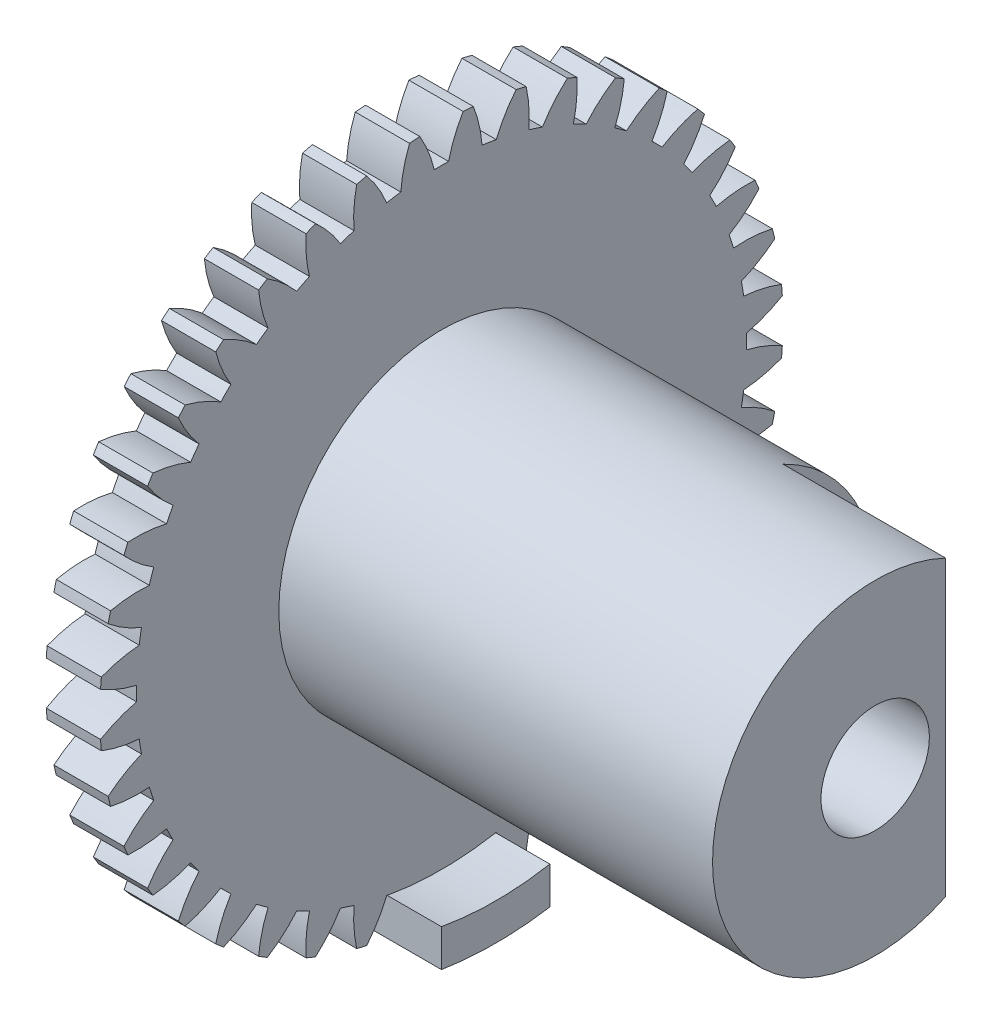
SolidWorks part; units mm, degrees
ref_plane "Plane1" through (0, 0, 0) normal (0, 0, 1) x (1, 0, 0)
ref_plane "Plane2" through (0, 0, 0) normal (0, 1, 0) x (1, 0, 0)
ref_plane "Plane3" through (0, 0, 0) normal (1, 0, 0) x (0, 0, -1)
sketch "HoldingSke" plane through (0, 0, 0) normal (0, 1, 0) x (1, 0, 0)
  line L0 (0, 0) -> (2.5535, -2.1426)
  line L1 (-15, 0) -> (100, 0) construction
  line L2 (0, 0) -> (-2.1039, 2.3779)
  line L3 (0, 0) -> (-11.863, 4.5341)
  line L4 (0, 0) -> (6.6156, 5.5511)
  line L5 (0, 0) -> (-46.8476, -17.4728)
  line L6 (0, 0) -> (-0.829, -0.5593)
  line L7 (-2.1039, 2.3779) -> (8.6586, 51.2059)
  line L8 (-76.2, 54.61) -> (-75.9, 54.61)
  line L9 (-71.009, 38.7566) -> (-53.1078, 45.2721)
  line L10 (-76.2, 71.12) -> (104.1128, 71.12)
  line L11 (0, 0) -> (-1, 0)
  line L12 (-76.2, 101.6) -> (-76.19, 101.6)
  line L13 (24.9733, 27.94) -> (52.9518, 28.4284)
  line L14 (24.9733, 27.94) -> (24.9743, 27.94)
  line L15 (24.9733, 27.94) -> (100.4006, 29.5858)
  line L16 (-63.627, -0.3) -> (-12.827, -0.3)
  circle A0 centre (0, 0) radius 1
  circle A1 centre (0, 0) radius 5.624
  circle A2 centre (0, 0) radius 37.5
  circle A3 centre (0, 0) radius 1
  dimension "MHD" = 11.248
  dimension "Hub_dia" = 75
  dimension "Bore" = 2
  dimension "MBD" = 2
  dimension "Num_teeth" = 40
  dimension "Pitch" = 3.3333
  dimension "Overall_len" = 50
  dimension "Show_teeth" = 40
  dimension "Thickness" = 1
  dimension "OAL" = 50.0001
  dimension "T_dim" = 0.3
  dimension "Ap" = 20
  dimension "H" = 19.05
  dimension "Pitch_radius" = 180.3128
  dimension "Width" = 1
  dimension "Backlash" = 0.01
  dimension "Addendum_fac" = 1
  dimension "Dedendum_fac" = 1.25
  dimension "Clearance_fac" = 0.25
  dimension "Dedendum_add" = 0.001
  dimension "Module" = 0.3
sketch "BasProSke" plane through (0, 0, 0) normal (0, 1, 0) x (1, 0, 0)
  line L0 (-10, 0) -> (60, 0) construction
  line L1 (0, 0) -> (0, 6.3)
  line L2 (0, 0) -> (1, 0)
  line L3 (1, 0) -> (1, 6.3)
  line L4 (1, 6.3) -> (0, 6.3)
  dimension "Thickness" = 1
  dimension "Diameter" = 12.6
revolve "Base-Revolve" add sketch "BasProSke" angle 360 about L0
sketch "TooCutSke" plane through (0, 0, 0) normal (1, 0, 0) x (0, 0, -1)
  line L1 (0, 0) -> (0, 107) construction
  line L2 (0, 0) -> (-0.2531, 5.9947) construction
  line L3 (0, 0) -> (-0.9409, 11.9551) construction
  line L4 (-0.2531, 5.9947) -> (-0.4704, 5.9776) construction
  arc A0 (0.1321, 5.6224) -> (-0.1321, 5.6224) centre (0, 0) ccw
  arc A1 (0.4141, 6.3118) -> (-0.4141, 6.3118) centre (0, 0) ccw
  circle A2 centre (0, 0) radius 6 construction
  circle A3 centre (0, 0) radius 5.6382 construction
  arc A4 (-0.1321, 5.6224) -> (-0.4141, 6.3118) centre (-2.4676, 5.0695) ccw
  arc A5 (0.4141, 6.3118) -> (0.1321, 5.6224) centre (2.4676, 5.0695) ccw
  dimension "Root_dia" = 11.248
  dimension "Overcut_dia" = 12.6508
  dimension "Pitch_dia" = 12
  dimension "Base_dia" = 11.2763
  dimension "Flank_rad" = 2.4
  dimension "Half_ang" = 4.5
  dimension "Half_CT" = 0.2181
extrude "ToothCut" cut sketch "TooCutSke" along normal through all
fillet "Breaks" [suppressed] radius 0.006
fillet "RootFillets" [suppressed] radius 0.076
pattern_circular "TeethCuts" count 40 every 9 about axis through (-10, 0, 0) along (1, 0, 0) of "ToothCut", "RootFillets", "Breaks"
sketch "HubNeaOneSke" plane through (0, 0, 0) normal (-1, 0, 0) x (0, 0, 1)
  circle A0 centre (0, 0) radius 5.624
  dimension "Diameter" = 11.248
extrude "HubNearOne" [suppressed] add sketch "HubNeaOneSke" along normal blind 49.0001
sketch "HubNeaBotSke" plane through (0, 0, 0) normal (-1, 0, 0) x (0, 0, 1)
  circle A0 centre (0, 0) radius 5.624
  dimension "Diameter" = 11.248
extrude "HubNearBoth" [suppressed] add sketch "HubNeaBotSke" along normal blind 24.5
ref_plane "FarPln" through (1, 0, 0) normal (1, 0, 0) x (0, 0, -1)
sketch "HubFarSke" plane through (1, 0, 0) normal (1, 0, 0) x (0, 0, -1)
  circle A0 centre (0, 0) radius 5.624
  dimension "Diameter" = 11.248
extrude "HubFar" [suppressed] add sketch "HubFarSke" along normal blind 24.5
sketch "BorSke" plane through (0, 0, 0) normal (1, 0, 0) x (0, 0, -1)
  circle A0 centre (0, 0) radius 1
  dimension "Diameter" = 2
extrude "Bore" cut sketch "BorSke" along normal mid plane 100.0001
sketch "KeySke" plane through (0, 0, 0) normal (1, 0, 0) x (0, 0, -1)
  line L0 (-0.4, 0) -> (-0.4, 1.3)
  line L1 (-0.4, 1.3) -> (0.4, 1.3)
  line L2 (0.4, 1.3) -> (0.4, 0)
  line L3 (0, 0) -> (0, 34) construction
  line L4 (-0.4, 0) -> (0.4, 0)
  dimension "Offset" = 1.3
  dimension "Width" = 0.8
extrude "Keyway" [suppressed] cut sketch "KeySke" along normal mid plane 100.0001
pattern_circular "Keyway2" [suppressed] count 2 every 90 about axis through (-10, 0, 0) along (1, 0, 0)
sketch "Schizzo1" plane through (1, 0, 0) normal (1, 0, 0) x (0, 0, -1)
  circle A0 centre (0, 0) radius 1
  circle A1 centre (0, 0) radius 3
  circle A2 centre (0, 0) radius 1 construction
  dimension "D1" = 6
extrude "Estrusione-Estrusione1" add sketch "Schizzo1" along normal blind 8
sketch "Schizzo3" plane through (9, 0, 0) normal (1, 0, 0) x (0, 0, -1)
  line L0 (1.3, -2.7037) -> (1.3, 2.7037)
  circle A0 centre (0, 0) radius 3 construction
  arc A1 (1.3, -2.7037) -> (1.3, 2.7037) centre (0, 0) ccw
  dimension "D1" = 1.3
extrude "Taglio-Estrusione2" cut sketch "Schizzo3" against normal blind 3
sketch "Schizzo4" plane through (0, 0, 0) normal (-1, 0, 0) x (0, 0, 1)
  line L0 (-1, -5.5344) -> (-1, -6.2201)
  line L1 (1, -5.5344) -> (1, -6.2201)
  arc A0 (-1, -5.5344) -> (1, -5.5344) centre (0, 0) ccw
  arc A1 (-1, -6.2201) -> (1, -6.2201) centre (0, 0) ccw
  circle A2 centre (0, 0) radius 1 construction
extrude "Estrusione-Estrusione2" add sketch "Schizzo4" against normal blind 2
sketch "Schizzo5" plane through (9, 0, 0) normal (1, 0, 0) x (0, 0, -1)
  circle A0 centre (0, 0) radius 1
  circle A1 centre (0, 0) radius 1 construction
extrude "Estrusione-Estrusione3" add sketch "Schizzo5" along normal blind 1 from offset 4 offset against normal yes
equation "' \"Module@HoldingSke\" = 6.35"
equation "' \"Num_teeth@HoldingSke\" = 12"
equation "' \"Ap@HoldingSke\" =  20"
equation "' \"Ap@HoldingSke\" = 20"
equation "' \"Width@HoldingSke\" = 0.5 * 25.4"
equation "' \"Hub_dia@HoldingSke\"= 1 * 25.4"
equation "' \"Hub_dia@HoldingSke\" = 1 * 25.4"
equation "' \"Overall_len@HoldingSke\" = 1.0 * 25.4"
equation "' \"Bore@HoldingSke\" = 0.75 * 25.4"
equation "' \"T_dim@HoldingSke\" = 0.1 * 25.4"
equation "' \"Width@KeySke\" = 0.25 * 25.4"
equation "' \"Show_teeth@HoldingSke\" = 13"
equation "' \"Backlash@HoldingSke\" = 0.009 * 25.4"
equation "' \"Addendum_fac@HoldingSke\" = 1.0"
equation "' \"Dedendum_fac@HoldingSke\" = 1.25"
equation "' \"Dedendum_add@HoldingSke\" = 0.00005 * 25.4"
equation "' \"Clearance_fac@HoldingSke\" = 0.25"
equation "\"Pitch@HoldingSke\" = 1 / \"Module@HoldingSke\""
equation "\"Overcut_dia@TooCutSke\" = (\"Num_teeth@HoldingSke\" + 2 * \"Addendum_fac@HoldingSke\") / \"Pitch@HoldingSke\" + 0.002 * 25.4"
equation "\"Pitch_dia@TooCutSke\" = \"Num_teeth@HoldingSke\" / \"Pitch@HoldingSke\""
equation "\"Base_dia@TooCutSke\" = \"Num_teeth@HoldingSke\" / \"Pitch@HoldingSke\" * cos((\"Ap@HoldingSke\"  * 3.14159265 / 180))"
equation "\"Root_dia@TooCutSke\" = (\"Num_teeth@HoldingSke\" + 2) / \"Pitch@HoldingSke\" - 2 * (\"Addendum_fac@HoldingSke\" + \"Dedendum_fac@HoldingSke\") / \"Pitch@HoldingSke\" - \"Dedendum_add@HoldingSke\" * 2"
equation "\"Half_ang@TooCutSke\" = 180 / \"Num_teeth@HoldingSke\""
equation "\"Half_CT@TooCutSke\" = \"Num_teeth@HoldingSke\" / \"Pitch@HoldingSke\" * sin((3.14159265 / 2 / \"Num_teeth@HoldingSke\")) / 2 - 7 * \"Backlash@HoldingSke\" / 4"
equation "\"Flank_rad@TooCutSke\" = \"Num_teeth@HoldingSke\" / \"Pitch@HoldingSke\" / 5"
equation "\"Radius@RootFillets\" = \"Clearance_fac@HoldingSke\" / \"Pitch@HoldingSke\" + \"Dedendum_add@HoldingSke\""
equation "\"Break_rad@Breaks\" = 0.02 / \"Pitch@HoldingSke\""
equation "\"Thickness@HoldingSke\" = \"Width@HoldingSke\""
equation "\"OAL@HoldingSke\" = \"Thickness@HoldingSke\""
equation "\"MHD@HoldingSke\" = (\"Num_teeth@HoldingSke\" + 2) / \"Pitch@HoldingSke\" - 2 * (\"Addendum_fac@HoldingSke\" + \"Dedendum_fac@HoldingSke\")  / \"Pitch@HoldingSke\" - \"Dedendum_add@HoldingSke\" * 2"
equation "\"MBD@HoldingSke\" = (\"Num_teeth@HoldingSke\" + 2) / \"Pitch@HoldingSke\" - 2 * (\"Addendum_fac@HoldingSke\" + \"Dedendum_fac@HoldingSke\")  / \"Pitch@HoldingSke\" - \"Dedendum_add@HoldingSke\" * 2 - 0.002 * 25.4"
equation "\"MHD@HoldingSke\" = ((sgn( \"MHD@HoldingSke\" - \"Hub_dia@HoldingSke\" )-1)*( \"MHD@HoldingSke\" - \"Hub_dia@HoldingSke\" ))/-2+ \"Hub_dia@HoldingSke\""
equation "\"MBD@HoldingSke\" = ((sgn( \"MBD@HoldingSke\" - \"Bore@HoldingSke\" )-1)*( \"MBD@HoldingSke\" - \"Bore@HoldingSke\" ))/-2+ \"Bore@HoldingSke\""
equation "\"OAL@HoldingSke\" = ((sgn( \"OAL@HoldingSke\" - \"Overall_len@HoldingSke\" )+1)*( \"OAL@HoldingSke\" - \"Overall_len@HoldingSke\" ))/2 + \"Overall_len@HoldingSke\" + 0.000002 * 25.4"
equation "\"Num_teeth@TeethCuts\" = int( \"Show_teeth@HoldingSke\" ) + 1"
equation "\"Num_teeth@TeethCuts\" = ((sgn( \"Num_teeth@TeethCuts\" - \"Num_teeth@HoldingSke\" )-1)*( \"Num_teeth@TeethCuts\" - \"Num_teeth@HoldingSke\" ))/-2+ \"Num_teeth@HoldingSke\""
equation "\"Num_teeth@TeethCuts\" = ((sgn( \"Num_teeth@TeethCuts\" - 2.0)+1)*( \"Num_teeth@TeethCuts\" - 2.0))/2 +2.0"
equation "\"Angle@TeethCuts\" = 360.0 / \"Num_teeth@HoldingSke\""
equation "\"Diameter@BasProSke\" = (\"Num_teeth@HoldingSke\" + 2 * \"Addendum_fac@HoldingSke\") / \"Pitch@HoldingSke\""
equation "\"Thickness@BasProSke\"  = \"Thickness@HoldingSke\""
equation "' \"Fillet_rad@BasProSke\" =  \"Thickness@HoldingSke\" * 0.05"
equation "' \"Fillet_rad@BasProSke\" = \"Thickness@HoldingSke\" * 0.05"
equation "\"MHD@HoldingSke\" = ((sgn( \"MHD@HoldingSke\" - \"Root_dia@TooCutSke\" )-1)*( \"MHD@HoldingSke\" - \"Root_dia@TooCutSke\" ))/-2+ \"Root_dia@TooCutSke\""
equation "\"Diameter@HubNeaOneSke\" = \"MHD@HoldingSke\""
equation "\"Length@HubNearOne\" = \"OAL@HoldingSke\" - \"Thickness@BasProSke\""
equation "\"Diameter@HubNeaBotSke\" = \"MHD@HoldingSke\""
equation "\"Length@HubNearBoth\" = ( \"OAL@HoldingSke\" - \"Thickness@BasProSke\" ) / 2.0"
equation "\"Thickness@FarPln\" = \"Thickness@BasProSke\""
equation "\"Diameter@HubFarSke\" = \"MHD@HoldingSke\""
equation "\"Length@HubFar\" = ( \"OAL@HoldingSke\" - \"Thickness@BasProSke\" ) / 2.0"
equation "\"Diameter@BorSke\" = \"MBD@HoldingSke\""
equation "\"D1@Bore\" = \"OAL@HoldingSke\" * 2.0"
equation "\"D1@Keyway\" = \"OAL@HoldingSke\" * 2.0"
equation "\"Offset@KeySke\" = \"T_dim@HoldingSke\" + \"MBD@HoldingSke\" / 2.0"
